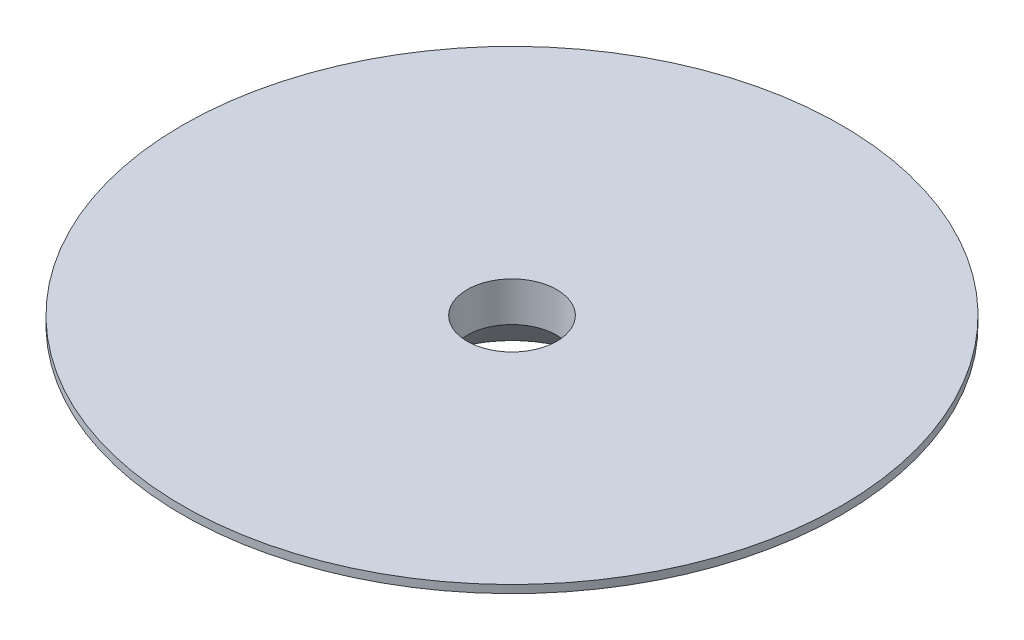
SolidWorks part; units mm, degrees
material "ABS"
ref_plane "Plan de face" through (0, 0, 0) normal (0, 0, 1) x (1, 0, 0)
ref_plane "Plan de dessus" through (0, 0, 0) normal (0, 1, 0) x (1, 0, 0)
ref_plane "Plan de droite" through (0, 0, 0) normal (1, 0, 0) x (0, 0, -1)
sketch "Esquisse1" plane through (0, 0, 0) normal (0, 0, 1) x (1, 0, 0)
  line L0 (0, 0) -> (0, -3.3) construction
  line L1 (0, -3.3) -> (8.2156, -3.3)
  line L2 (8.2156, -3.3) -> (12.5, -0.3)
  line L3 (12.5, 0) -> (0, 0)
  line L4 (0, 0) -> (0, -3.3)
  line L5 (12.5, -0.3) -> (12.5, 0)
  dimension "D1" = 12.5
  dimension "D2" = 3.3
  dimension "D3" = 35
  dimension "D4" = 0.3
revolve "Révolution1" add sketch "Esquisse1" angle 360 about L0
fillet "Congé1" radius 10 1 edges at (-8.2156, -3.3, 0)
hole_wizard "Fraisage pour vis à tête fraisée M31" positions "Esquisse3" profile "Esquisse2" countersink size "M3" standard "Iso" end condition through all
sketch "Esquisse3" plane through (0, -3.3, 0) normal (0, -1, 0) x (1, 0, 0)
  point P0 (0, 0)
sketch "Esquisse2" plane through (0, -3.3, 0) normal (1, 0, 0) x (0, 0, -1)
  line L0 (0, 0) -> (0, 3.3)
  line L1 (0, 3.3) -> (1.7, 3.3)
  line L2 (1.7, 3.3) -> (1.7, 1.8)
  line L3 (1.7, 1.8) -> (3.5, 0)
  line L5 (3.5, 0) -> (0, 0)
  line L6 (-1.7, 1.8) -> (-3.5, 0) construction
  line L11 (0, -6.35) -> (0, 107.95) construction
  dimension "Diamètre du perçage jusqu'au prochain" = 3.4
  dimension "Profondeur du perçage jusqu'au prochain" = 3.3
  dimension "Diamètre du fraisage entrant" = 7
  dimension "Angle du fraisage entrant" = 90
